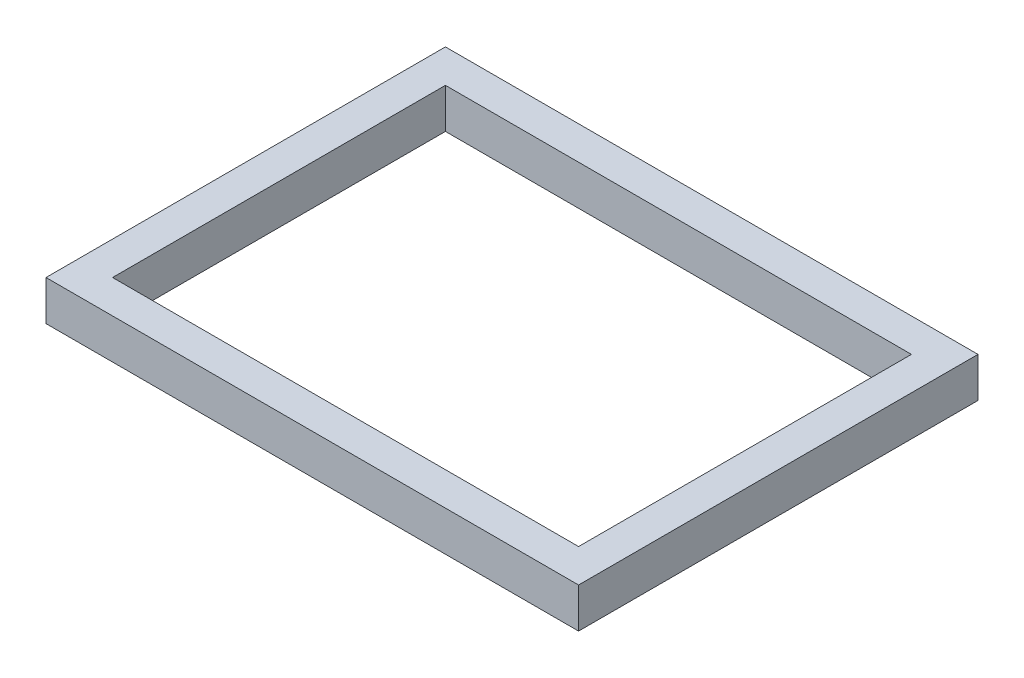
SolidWorks part; units mm, degrees
ref_plane "Front Plane" through (0, 0, 0) normal (0, 0, 1) x (1, 0, 0)
ref_plane "Top Plane" through (0, 0, 0) normal (0, 1, 0) x (1, 0, 0)
ref_plane "Right Plane" through (0, 0, 0) normal (1, 0, 0) x (0, 0, -1)
sketch "Sketch1" plane through (0, 0, 0) normal (0, 1, 0) x (1, 0, 0)
  line L0 (19.6102, 10.9802) -> (19.6102, -49.0198) construction
  line L1 (-20.3898, 10.9802) -> (59.6102, 10.9802)
  line L2 (-20.3898, 10.9802) -> (-20.3898, -49.0198)
  line L3 (-20.3898, -49.0198) -> (59.6102, -49.0198)
  line L4 (59.6102, 10.9802) -> (59.6102, -49.0198)
  line L5 (19.6102, -19.0198) -> (59.6102, -19.0198) construction
  line L7 (-15.3898, 5.9802) -> (54.6102, 5.9802)
  line L8 (-15.3898, 5.9802) -> (-15.3898, -44.0198)
  line L9 (-15.3898, -44.0198) -> (54.6102, -44.0198)
  line L10 (54.6102, 5.9802) -> (54.6102, -44.0198)
  line L11 (-15.3898, 5.9802) -> (54.6102, -44.0198) construction
  line L12 (-15.3898, -44.0198) -> (54.6102, 5.9802) construction
  dimension "D1" = 80
  dimension "D2" = 60
  dimension "D3" = 70
  dimension "D4" = 50
extrude "Boss-Extrude1" add sketch "Sketch1" along normal blind 6
